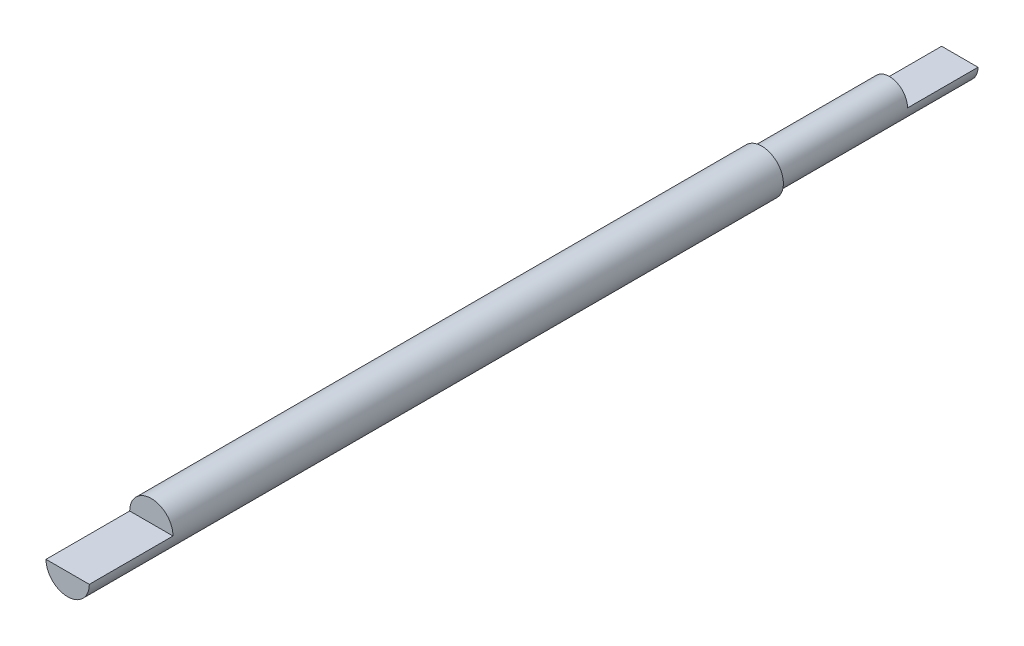
SolidWorks part; units mm, degrees
ref_plane "Front Plane" through (0, 0, 0) normal (0, 0, 1) x (1, 0, 0)
ref_plane "Top Plane" through (0, 0, 0) normal (0, 1, 0) x (1, 0, 0)
ref_plane "Right Plane" through (0, 0, 0) normal (1, 0, 0) x (0, 0, -1)
sketch "Sketch1" plane through (0, 0, 0) normal (0, 0, 1) x (1, 0, 0)
  circle A0 centre (0, 0) radius 4.7625
  dimension "D1" = 9.525
extrude "Boss-Extrude1" add sketch "Sketch1" along normal blind 196.25
sketch "Sketch2" plane through (0, 0, 196.25) normal (0, 0, 1) x (1, 0, 0)
  line L1 (-4.7625, 0) -> (4.7625, 0)
  circle A0 centre (0, 0) radius 4.7625
  dimension "D2" = 9.525
extrude "Cut-Extrude1" cut sketch "Sketch2" against normal blind 18.41
sketch "Sketch3" plane through (0, 0, 0) normal (0, 0, -1) x (-1, 0, 0)
  circle A0 centre (0, 0) radius 4.7625
  circle A1 centre (0, 0) radius 4
  dimension "D1" = 9.525
  dimension "D2" = 8
extrude "Cut-Extrude2" cut sketch "Sketch3" against normal blind 43.57
sketch "Sketch4" plane through (0, 0, 0) normal (0, 0, -1) x (-1, 0, 0)
  line L0 (-4, 0) -> (4, 0)
  circle A0 centre (0, 0) radius 4
  circle M1 centre (0, 0) radius 4
  dimension "D1" = 8
extrude "Cut-Extrude3" cut sketch "Sketch4" against normal blind 15.5 contours L0 M1
